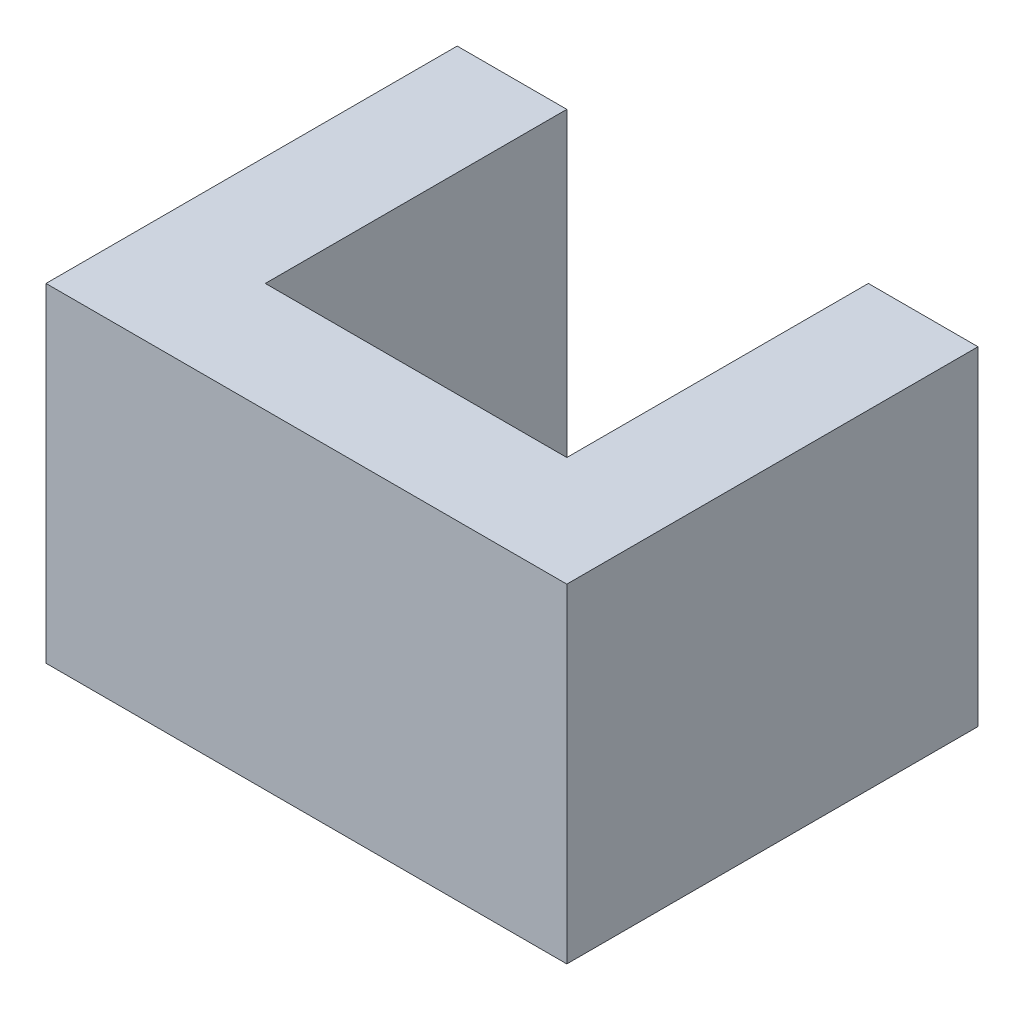
SolidWorks part; units mm, degrees
ref_plane "Front Plane" through (0, 0, 0) normal (0, 0, 1) x (1, 0, 0)
ref_plane "Top Plane" through (0, 0, 0) normal (0, 1, 0) x (1, 0, 0)
ref_plane "Right Plane" through (0, 0, 0) normal (1, 0, 0) x (0, 0, -1)
sketch "Sketch1" plane through (0, 0, 0) normal (0, 1, 0) x (1, 0, 0)
  line L0 (-9.5, 0) -> (9.5, 0)
  line L1 (9.5, 0) -> (9.5, 15)
  line L2 (-9.5, 0) -> (-9.5, 15)
  line L3 (-9.5, 15) -> (-5.5, 15)
  line L4 (-5.5, 15) -> (-5.5, 4)
  line L5 (-5.5, 4) -> (5.5, 4)
  line L6 (5.5, 4) -> (5.5, 15)
  line L7 (5.5, 15) -> (9.5, 15)
  dimension "D1" = 11
  dimension "D2" = 15
  dimension "D3" = 4
  dimension "D4" = 4
extrude "Boss-Extrude1" add sketch "Sketch1" along normal blind 12
